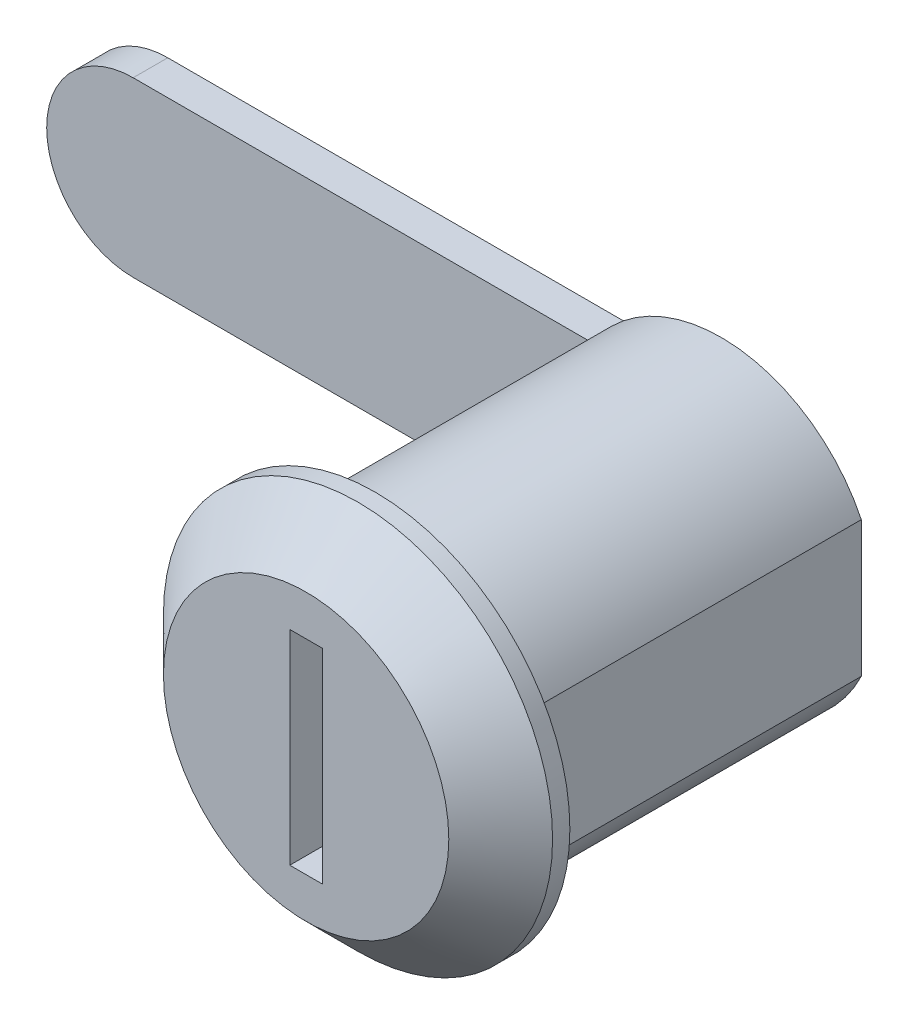
SolidWorks part; units mm, degrees
material "冷轧钢板"
ref_plane "前视基准面" through (0, 0, 0) normal (0, 0, 1) x (1, 0, 0)
ref_plane "上视基准面" through (0, 0, 0) normal (0, 1, 0) x (1, 0, 0)
ref_plane "右视基准面" through (0, 0, 0) normal (1, 0, 0) x (0, 0, -1)
sketch "草图1" plane through (0, 0, 0) normal (0, 0, 1) x (1, 0, 0)
  circle A0 centre (0, 0) radius 11.25
  dimension "D1" = 22.5
extrude "凸台-拉伸1" add sketch "草图1" along normal blind 4
sketch "草图2" plane through (0, 0, 4) normal (0, 0, 1) x (1, 0, 0)
  line L1 (-0.945, -5.9032) -> (0.945, -5.9032)
  line L2 (-0.945, -5.9032) -> (-0.945, 5.9032)
  line L3 (-0.945, 5.9032) -> (0.945, 5.9032)
  line L4 (0.945, -5.9032) -> (0.945, 5.9032)
  line L5 (-0.945, -5.9032) -> (0.945, 5.9032) construction
  line L6 (-0.945, 5.9032) -> (0.945, -5.9032) construction
  point P0 (0, 0)
extrude "切除-拉伸1" cut sketch "草图2" against normal blind 2
sketch "草图3" plane through (0, 0, 0) normal (0, 0, -1) x (-1, 0, 0)
  line L0 (0, 11.25) -> (0, -11.25) construction
  line L1 (-8.1, -3.923) -> (-8.1, 3.923)
  line L2 (8.1, -3.923) -> (8.1, 3.923)
  arc A0 (-8.1, -3.923) -> (8.1, -3.923) centre (0, 0) ccw
  circle A1 centre (0, 0) radius 11.25 construction
  arc A2 (8.1, 3.923) -> (-8.1, 3.923) centre (0, 0) ccw
  dimension "D1" = 18
  dimension "D2" = 16.2
  dimension "D3" = 7.846
extrude "凸台-拉伸2" add sketch "草图3" along normal blind 20
sketch "草图4" plane through (0, 0, -20) normal (0, 0, -1) x (-1, 0, 0)
  line L0 (0, 0) -> (34, 0) construction
  line L1 (0, 5) -> (34, 5)
  line L2 (0, -5) -> (34, -5)
  arc A0 (0, 5) -> (0, -5) centre (0, 0) ccw
  arc A1 (34, -5) -> (34, 5) centre (34, 0) ccw
  point P3 (17, 0)
  point P8 (39, 0)
  dimension "D1" = 10
  dimension "D2" = 39
extrude "凸台-拉伸3" add sketch "草图4" along normal blind 2
chamfer "倒角1" distance 3 angle 45 1 edges at (11.25, 0, 4)
